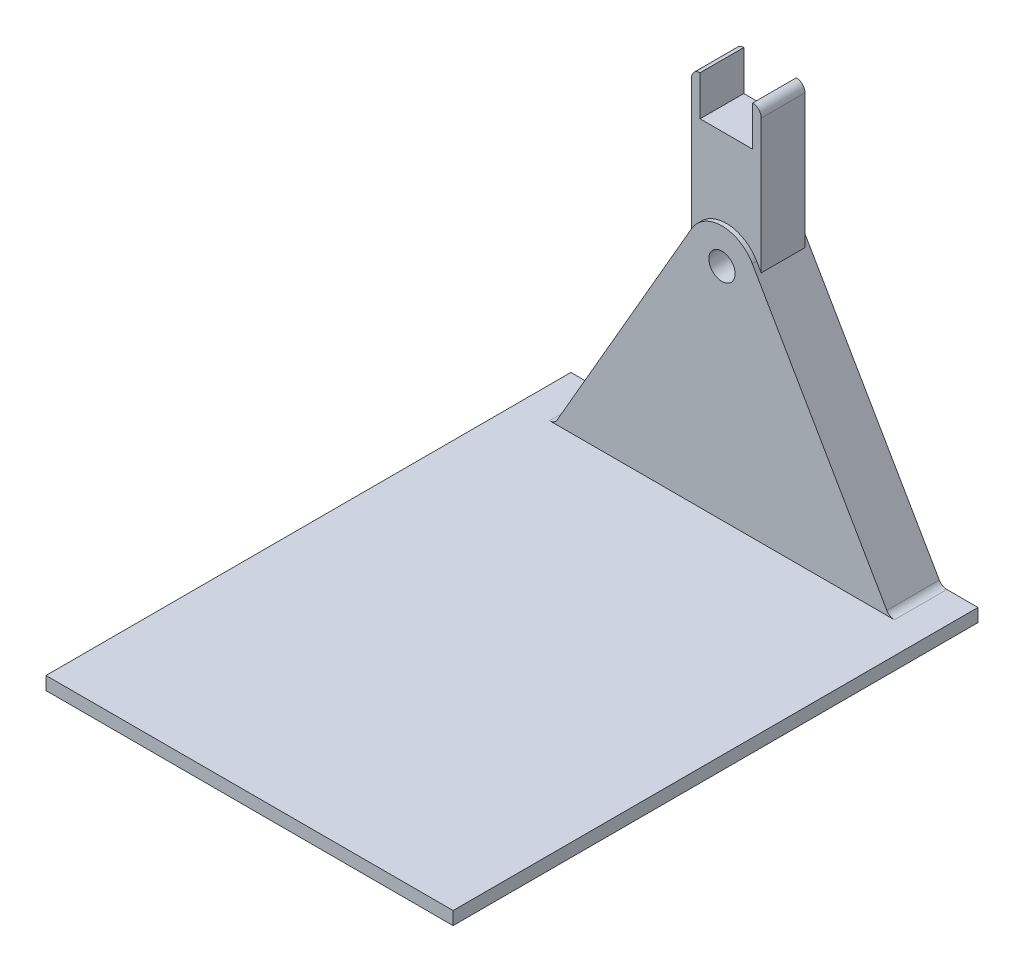
SolidWorks part; units mm, degrees
ref_plane "前基準面" through (0, 0, 0) normal (0, 0, 1) x (1, 0, 0)
ref_plane "上基準面" through (0, 0, 0) normal (0, 1, 0) x (1, 0, 0)
ref_plane "右基準面" through (0, 0, 0) normal (1, 0, 0) x (0, 0, -1)
sketch "草圖1" plane through (0, 0, 0) normal (0, 0, 1) x (1, 0, 0)
  line L0 (-3.4641, 10.5369) -> (-19.134, -16.6041)
  line L1 (-18.2679, -18.1041) -> (18.2679, -18.1041)
  line L2 (0, -18.1041) -> (0, 16.5369)
  line L3 (3.4641, 10.5369) -> (19.134, -16.6041)
  arc A0 (-19.134, -16.6041) -> (-18.2679, -18.1041) centre (-18.2679, -17.1041) ccw
  arc A1 (19.134, -16.6041) -> (18.2679, -18.1041) centre (18.2679, -17.1041) cw
  arc A2 (3.4641, 10.5369) -> (-3.4641, 10.5369) centre (0, 8.5369) ccw
  point P5 (-20, -18.1041)
  dimension "D3" = 1
  dimension "D4" = 4
  dimension "D1" = 40
  dimension "D2" = 20
extrude "填料-伸長1" add sketch "草圖1" along normal mid plane 6 contours L3 A2 L2 L1 A1 | L2 A2 L0 A0 L1
sketch "草圖2" plane through (0, 0, 0) normal (0, 0, 1) x (1, 0, 0)
  line L0 (-3.9884, 8.8414) -> (-3.9884, 24.9476)
  line L2 (-3, 25.9475) -> (-3, 21.3865)
  line L3 (-3, 21.3865) -> (3, 21.3865)
  line L4 (0, 21.3865) -> (0, 12.5369)
  line L5 (3, 25.9475) -> (3, 21.3865)
  line L7 (3.9884, 8.8414) -> (3.9884, 24.9476)
  line L8 (-3.9884, 8.8414) -> (3.9884, 8.8414)
  arc A0 (3.4641, 10.5369) -> (-3.4641, 10.5369) centre (0, 8.5369) ccw construction
  arc A1 (-3, 25.9475) -> (-3.9884, 24.9476) centre (-2.9884, 24.9476) ccw
  arc A2 (3, 25.9475) -> (3.9884, 24.9476) centre (2.9884, 24.9476) cw
  point P17 (0, 21.3865)
  point P18 (2.9884, 25.8879)
  dimension "D1" = 1
  dimension "D2" = 6
extrude "填料-伸長2" add sketch "草圖2" along normal mid plane 5
sketch "草圖3" plane through (0, -18.1041, 0) normal (0, -1, 0) x (1, 0, 0)
  line L0 (-18.2679, -3) -> (18.2679, -3) construction
  line L1 (-23.2679, -3) -> (23.2679, -3)
  line L2 (-23.2679, -3) -> (-23.2679, 57)
  line L3 (-23.2679, 57) -> (23.2679, 57)
  line L4 (23.2679, -3) -> (23.2679, 57)
  line L8 (18.2679, 3) -> (18.2679, -3) construction
  line L9 (-18.2679, 3) -> (-18.2679, -3) construction
  dimension "D1" = 0
  dimension "D2" = 5
  dimension "D3" = 5
  dimension "D4" = 60
extrude "填料-伸長3" add sketch "草圖3" against normal blind 1.5
fillet "圓角1" radius 1 2 edges at (-19.134, -16.6041, 0) (19.134, -16.6041, 0)
sketch "草圖4" plane through (0, 0, -3) normal (0, 0, -1) x (-1, 0, 0)
  circle A0 centre (0, 8.5369) radius 1.5
  dimension "D1" = 3
extrude "除料-伸長1" cut sketch "草圖4" against normal through all
